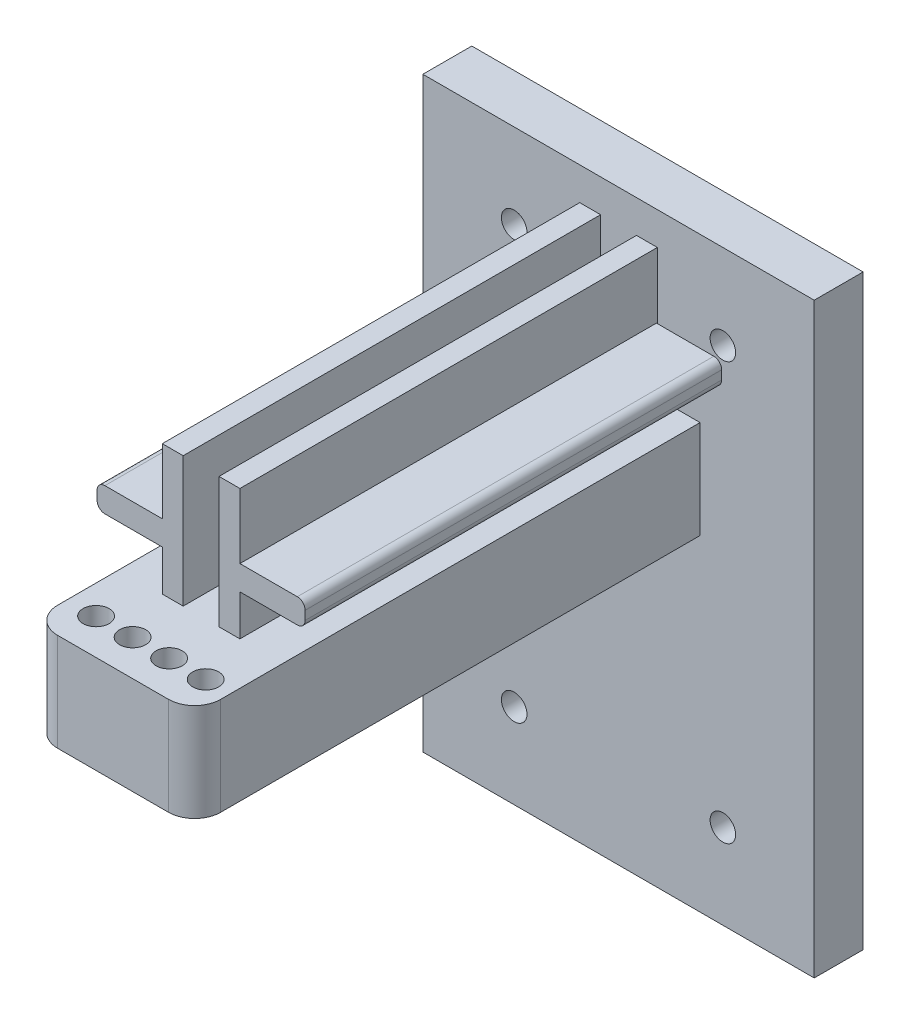
SolidWorks part; units mm, degrees
ref_plane "Front Plane" through (0, 0, 0) normal (0, 0, 1) x (1, 0, 0)
ref_plane "Top Plane" through (0, 0, 0) normal (0, 1, 0) x (1, 0, 0)
ref_plane "Right Plane" through (0, 0, 0) normal (1, 0, 0) x (0, 0, -1)
sketch "Sketch1" plane through (0, 0, 0) normal (0, 0, 1) x (1, 0, 0)
  line L1 (-19.05, -28.575) -> (19.05, -28.575)
  line L2 (-19.05, -28.575) -> (-19.05, 28.575)
  line L3 (-19.05, 28.575) -> (19.05, 28.575)
  line L4 (19.05, -28.575) -> (19.05, 28.575)
  line L5 (-19.05, -28.575) -> (19.05, 28.575) construction
  line L6 (-19.05, 28.575) -> (19.05, -28.575) construction
  point P0 (0, 0)
  dimension "D1" = 38.1
  dimension "D2" = 57.15
extrude "Boss-Extrude1" add sketch "Sketch1" along normal blind 4.7625
sketch "Sketch2" plane through (0, 0, 0) normal (0, 0, 1) x (1, 0, 0)
  line L0 (0, 0) -> (19.05, 0) construction
  line L7 (19.05, -28.575) -> (19.05, 28.575) construction
  line L9 (19.05, 28.575) -> (-19.05, 28.575) construction
  line L10 (0, 0) -> (0, 28.575) construction
  circle A4 centre (10.16, 20.32) radius 1.2446
  circle A5 centre (-10.16, 20.32) radius 1.2446
  circle A6 centre (10.16, -20.32) radius 1.2446
  circle A7 centre (-10.16, -20.32) radius 1.2446
  point P0 (0, 0)
  dimension "D1" = 10.16
  dimension "D2" = 2.4892
  dimension "D5" = 20.32
extrude "Cut-Extrude1" cut sketch "Sketch2" along normal blind 4.7625
sketch "Sketch4" plane through (0, 0, 4.7625) normal (0, 0, 1) x (1, 0, 0)
  line L0 (0, -28.575) -> (0, 28.575) construction
  line L1 (-19.05, -28.575) -> (19.05, -28.575) construction
  line L2 (19.05, 28.575) -> (-19.05, 28.575) construction
  line L3 (-19.05, 0) -> (19.05, 0) construction
  line L4 (-19.05, 28.575) -> (-19.05, -28.575) construction
  line L5 (19.05, -28.575) -> (19.05, 28.575) construction
  line L6 (-19.05, 3.175) -> (19.05, 3.175) construction
  line L7 (-7.9375, 3.175) -> (7.9375, 3.175)
  line L8 (-41.275, -41.275) -> (41.275, -41.275) construction
  line L9 (-41.275, -41.275) -> (-41.275, 41.275) construction
  line L10 (-41.275, 41.275) -> (41.275, 41.275) construction
  line L11 (41.275, -41.275) -> (41.275, 41.275) construction
  line L12 (-41.275, -41.275) -> (41.275, 41.275) construction
  line L13 (-41.275, 41.275) -> (41.275, -41.275) construction
  line L14 (-7.9375, 3.175) -> (-7.9375, 12.7)
  line L15 (7.9375, 3.175) -> (7.9375, 12.7)
  line L16 (-7.9375, 12.7) -> (7.9375, 12.7)
  point P14 (0, 0)
  point P20 (0, 0)
  point P23 (0, 12.7)
  dimension "D1" = 82.55
  dimension "D2" = 82.55
  dimension "D3" = 44.45
  dimension "D4" = 15.875
  dimension "D5" = 9.525
extrude "Boss-Extrude2" add sketch "Sketch4" along normal blind 49.2125
sketch "Sketch5" plane through (0, 12.7, 0) normal (0, 1, 0) x (1, 0, 0)
  line L0 (0, -4.7625) -> (0, -43.4412) construction
  line L1 (7.9375, -4.7625) -> (-7.9375, -4.7625) construction
  line L2 (7.9375, -53.975) -> (-7.9375, -53.975) construction
  line L3 (-7.9375, -42.8625) -> (-6.4135, -42.8625) construction
  line L4 (-7.9375, -53.975) -> (-7.9375, -4.7625) construction
  line L5 (7.9375, -53.975) -> (7.9375, -4.7625) construction
  line L6 (0, -42.8625) -> (0, -53.975) construction
  line L7 (0, -42.8625) -> (0, -53.975) construction
  line L8 (-3.8735, -42.8625) -> (7.9375, -42.8625) construction
  circle A4 centre (-5.1435, -50.4825) radius 1.27
  circle A14 centre (-1.5875, -50.4825) radius 1.27
  circle A16 centre (1.9685, -50.4825) radius 1.27
  circle A18 centre (5.5245, -50.4825) radius 1.27
  dimension "D2" = 5.1435
  dimension "D1" = 38.1
  dimension "D3" = 45.72
  dimension "D5" = 4
extrude "Cut-Extrude2" cut sketch "Sketch5" against normal up to next
fillet "Fillet2" radius 2.54 2 edges at (-7.9375, 7.9375, 53.975) (7.9375, 7.9375, 53.975)
ref_plane "Plane1" through (0, 0, 0) normal (-1, 0, 0) x (0, 0, 1)
sketch "Sketch8" plane through (0, 0, 4.7625) normal (0, 0, 1) x (1, 0, 0)
  line L0 (0, 28.575) -> (0, 12.7) construction
  line L1 (19.05, 28.575) -> (-19.05, 28.575) construction
  line L2 (7.9375, 12.7) -> (-7.9375, 12.7) construction
  line L3 (-4.572, 25.4) -> (4.572, 25.4) construction
  line L4 (5.3975, 12.7) -> (-5.3975, 12.7) construction
  line L5 (-3.7782, 12.7) -> (-1.7462, 12.7)
  line L6 (-4.572, 25.4) -> (4.572, 25.4) construction
  line L7 (-4.572, 25.4) -> (-4.572, 12.7) construction
  line L8 (-4.572, 12.7) -> (4.572, 12.7) construction
  line L9 (4.572, 25.4) -> (4.572, 12.7) construction
  line L10 (-4.572, 25.4) -> (4.572, 12.7) construction
  line L11 (-4.572, 12.7) -> (4.572, 25.4) construction
  line L12 (-3.7782, 12.7) -> (-3.7783, 25.3847)
  line L13 (-1.7462, 12.7) -> (-1.7463, 25.3847)
  line L14 (-3.7783, 25.3847) -> (-1.7463, 25.3847)
  line L15 (3.7783, 12.7) -> (1.7462, 12.7)
  line L16 (3.7783, 12.7) -> (3.7783, 25.3847)
  line L17 (3.7783, 25.3847) -> (1.7463, 25.3847)
  line L18 (1.7462, 12.7) -> (1.7463, 25.3847)
  point P9 (0, 25.4)
  point P13 (0, 19.05)
  point P22 (4.572, 22.2097)
  dimension "D1" = 9.144
  dimension "D2" = 12.7
  dimension "D3" = 1.5875
  dimension "D4" = 2.032
extrude "Boss-Extrude4" add sketch "Sketch8" along normal blind 40.64
sketch "Sketch9" plane through (-3.7782, 0, 0) normal (-1, 0, 0) x (0, 0, 1)
  line L0 (45.4025, 16.6687) -> (4.8502, 16.6687) construction
  line L1 (45.4025, 25.3847) -> (45.4025, 12.7) construction
  line L2 (45.4025, 12.7) -> (4.7625, 12.7) construction
  line L3 (4.8502, 16.6687) -> (45.4025, 16.6687)
  line L4 (4.8502, 16.6687) -> (4.8502, 19.05)
  line L5 (45.4025, 16.6687) -> (45.4025, 19.05)
  line L6 (4.8502, 19.05) -> (45.4025, 19.05)
  dimension "D1" = 3.9688
  dimension "D2" = 2.3813
extrude "Boss-Extrude5" add sketch "Sketch9" along normal blind 6.35
fillet "Fillet4" radius 0.762 2 edges at (-10.1282, 16.6687, 25.1264) (-10.1282, 19.05, 25.1264)
mirror "Mirror2" about plane through (0, 0, 0) normal (-1, 0, 0) of "Boss-Extrude5", "Fillet4"
